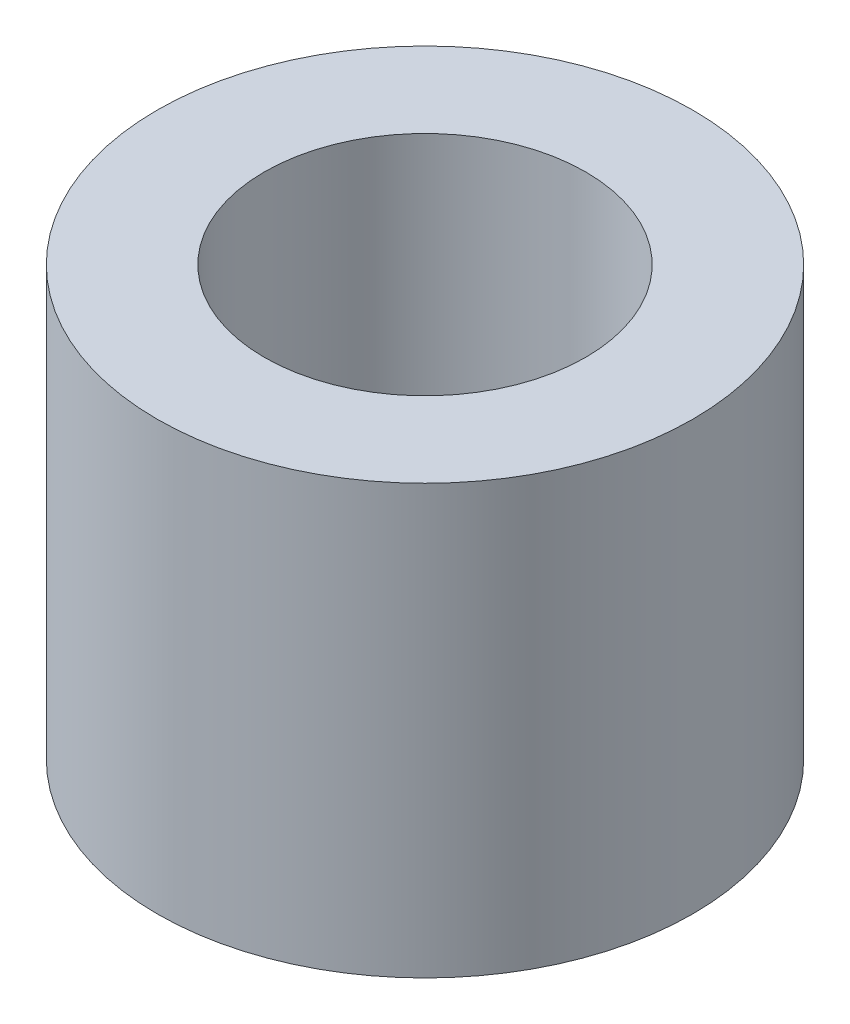
SolidWorks part; units mm, degrees
ref_plane "Спереди" through (0, 0, 0) normal (0, 0, 1) x (1, 0, 0)
ref_plane "Сверху" through (0, 0, 0) normal (0, 1, 0) x (1, 0, 0)
ref_plane "Справа" through (0, 0, 0) normal (1, 0, 0) x (0, 0, -1)
sketch "Эскиз1" plane through (0, 0, 0) normal (0, 1, 0) x (1, 0, 0)
  circle A0 centre (0, 0) radius 1.5
  circle A1 centre (0, 0) radius 2.5
extrude "Бобышка-Вытянуть1" add sketch "Эскиз1" along normal blind 4
